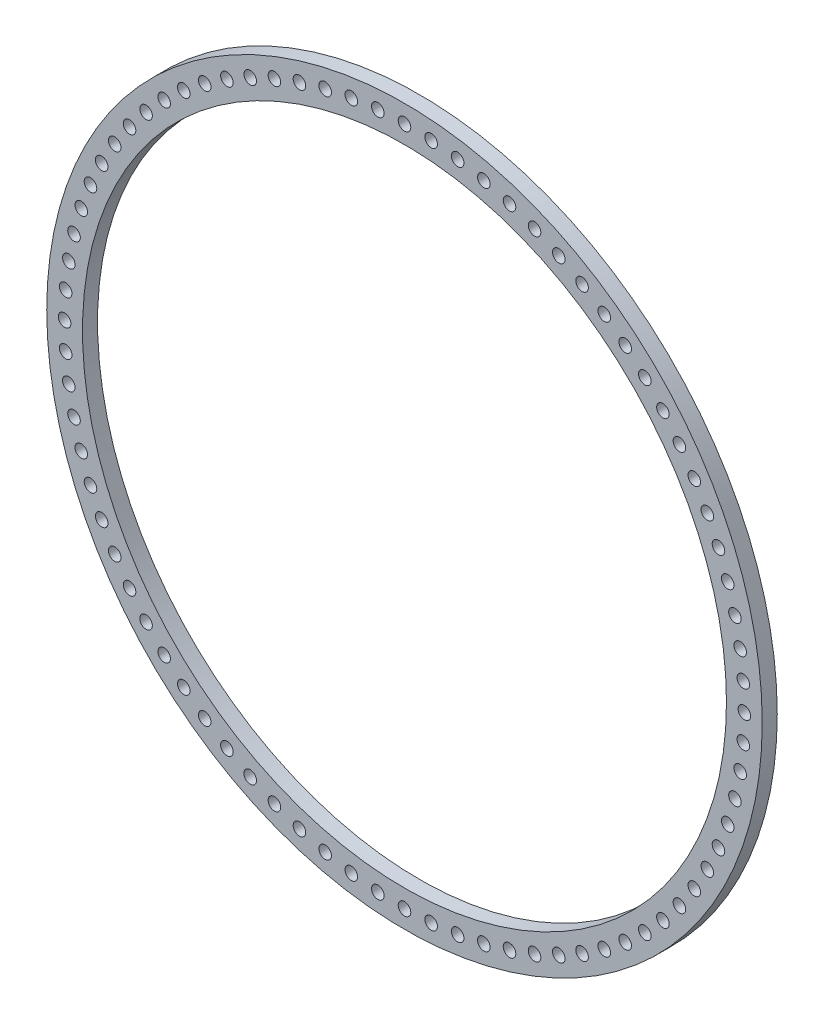
SolidWorks part; units mm, degrees
ref_plane "Front Plane" through (0, 0, 0) normal (0, 0, 1) x (1, 0, 0)
ref_plane "Top Plane" through (0, 0, 0) normal (0, 1, 0) x (1, 0, 0)
ref_plane "Right Plane" through (0, 0, 0) normal (1, 0, 0) x (0, 0, -1)
sketch "Model" plane through (0, 0, 0) normal (0, 0, 1) x (1, 0, 0)
  circle A0 centre (0, 0) radius 85.725
  circle A1 centre (90.2086, -7.0996) radius 1.6724
  circle A2 centre (89.3734, -14.1554) radius 1.6724
  circle A3 centre (87.9873, -21.1239) radius 1.6724
  circle A4 centre (86.0587, -27.9622) radius 1.6724
  circle A5 centre (83.5995, -34.6281) radius 1.6724
  circle A6 centre (80.625, -41.0805) radius 1.6724
  circle A7 centre (77.1533, -47.2796) radius 1.6724
  circle A8 centre (73.2059, -53.1872) radius 1.6724
  circle A9 centre (68.8072, -58.7669) radius 1.6724
  circle A10 centre (63.9843, -63.9843) radius 1.6724
  circle A11 centre (58.7669, -68.8072) radius 1.6724
  circle A12 centre (53.1872, -73.2059) radius 1.6724
  circle A13 centre (47.2796, -77.1533) radius 1.6724
  circle A14 centre (41.0805, -80.625) radius 1.6724
  circle A15 centre (34.6281, -83.5995) radius 1.6724
  circle A16 centre (27.9622, -86.0587) radius 1.6724
  circle A17 centre (21.1239, -87.9873) radius 1.6724
  circle A18 centre (14.1554, -89.3734) radius 1.6724
  circle A19 centre (7.0996, -90.2086) radius 1.6724
  circle A20 centre (0, -90.4875) radius 1.6724
  circle A21 centre (-7.0996, -90.2086) radius 1.6724
  circle A22 centre (-14.1554, -89.3734) radius 1.6724
  circle A23 centre (-21.1239, -87.9873) radius 1.6724
  circle A24 centre (-27.9622, -86.0587) radius 1.6724
  circle A25 centre (-34.6281, -83.5995) radius 1.6724
  circle A26 centre (-41.0805, -80.625) radius 1.6724
  circle A27 centre (-47.2796, -77.1533) radius 1.6724
  circle A28 centre (-53.1872, -73.2059) radius 1.6724
  circle A29 centre (-58.7669, -68.8072) radius 1.6724
  circle A30 centre (-63.9843, -63.9843) radius 1.6724
  circle A31 centre (-68.8072, -58.7669) radius 1.6724
  circle A32 centre (-73.2059, -53.1872) radius 1.6724
  circle A33 centre (-77.1533, -47.2796) radius 1.6724
  circle A34 centre (-80.625, -41.0805) radius 1.6724
  circle A35 centre (-83.5995, -34.6281) radius 1.6724
  circle A36 centre (-86.0587, -27.9622) radius 1.6724
  circle A37 centre (-87.9873, -21.1239) radius 1.6724
  circle A38 centre (-89.3734, -14.1554) radius 1.6724
  circle A39 centre (-90.2086, -7.0996) radius 1.6724
  circle A40 centre (-90.4875, 0) radius 1.6724
  circle A41 centre (-90.2086, 7.0996) radius 1.6724
  circle A42 centre (-89.3734, 14.1554) radius 1.6724
  circle A43 centre (-87.9873, 21.1239) radius 1.6724
  circle A44 centre (-86.0587, 27.9622) radius 1.6724
  circle A45 centre (-83.5995, 34.6281) radius 1.6724
  circle A46 centre (-80.625, 41.0805) radius 1.6724
  circle A47 centre (-77.1533, 47.2796) radius 1.6724
  circle A48 centre (-73.2059, 53.1872) radius 1.6724
  circle A49 centre (-68.8072, 58.7669) radius 1.6724
  circle A50 centre (-63.9843, 63.9843) radius 1.6724
  circle A51 centre (-58.7669, 68.8072) radius 1.6724
  circle A52 centre (-53.1872, 73.2059) radius 1.6724
  circle A53 centre (-47.2796, 77.1533) radius 1.6724
  circle A54 centre (-41.0805, 80.625) radius 1.6724
  circle A55 centre (-34.6281, 83.5995) radius 1.6724
  circle A56 centre (-27.9622, 86.0587) radius 1.6724
  circle A57 centre (-21.1239, 87.9873) radius 1.6724
  circle A58 centre (-14.1554, 89.3734) radius 1.6724
  circle A59 centre (-7.0996, 90.2086) radius 1.6724
  circle A60 centre (0, 90.4875) radius 1.6724
  circle A61 centre (7.0996, 90.2086) radius 1.6724
  circle A62 centre (14.1554, 89.3734) radius 1.6724
  circle A63 centre (21.1239, 87.9873) radius 1.6724
  circle A64 centre (27.9622, 86.0587) radius 1.6724
  circle A65 centre (34.6281, 83.5995) radius 1.6724
  circle A66 centre (41.0805, 80.625) radius 1.6724
  circle A67 centre (47.2796, 77.1533) radius 1.6724
  circle A68 centre (53.1872, 73.2059) radius 1.6724
  circle A69 centre (58.7669, 68.8072) radius 1.6724
  circle A70 centre (63.9843, 63.9843) radius 1.6724
  circle A71 centre (68.8072, 58.7669) radius 1.6724
  circle A72 centre (73.2059, 53.1872) radius 1.6724
  circle A73 centre (77.1533, 47.2796) radius 1.6724
  circle A74 centre (80.625, 41.0805) radius 1.6724
  circle A75 centre (83.5995, 34.6281) radius 1.6724
  circle A76 centre (86.0587, 27.9622) radius 1.6724
  circle A77 centre (87.9873, 21.1239) radius 1.6724
  circle A78 centre (89.3734, 14.1554) radius 1.6724
  circle A79 centre (90.2086, 7.0996) radius 1.6724
  circle A80 centre (90.4875, 0) radius 1.6724
  circle A81 centre (0, 0) radius 95.25
extrude "Boss-Extrude1" add sketch "Model" along normal blind 4
